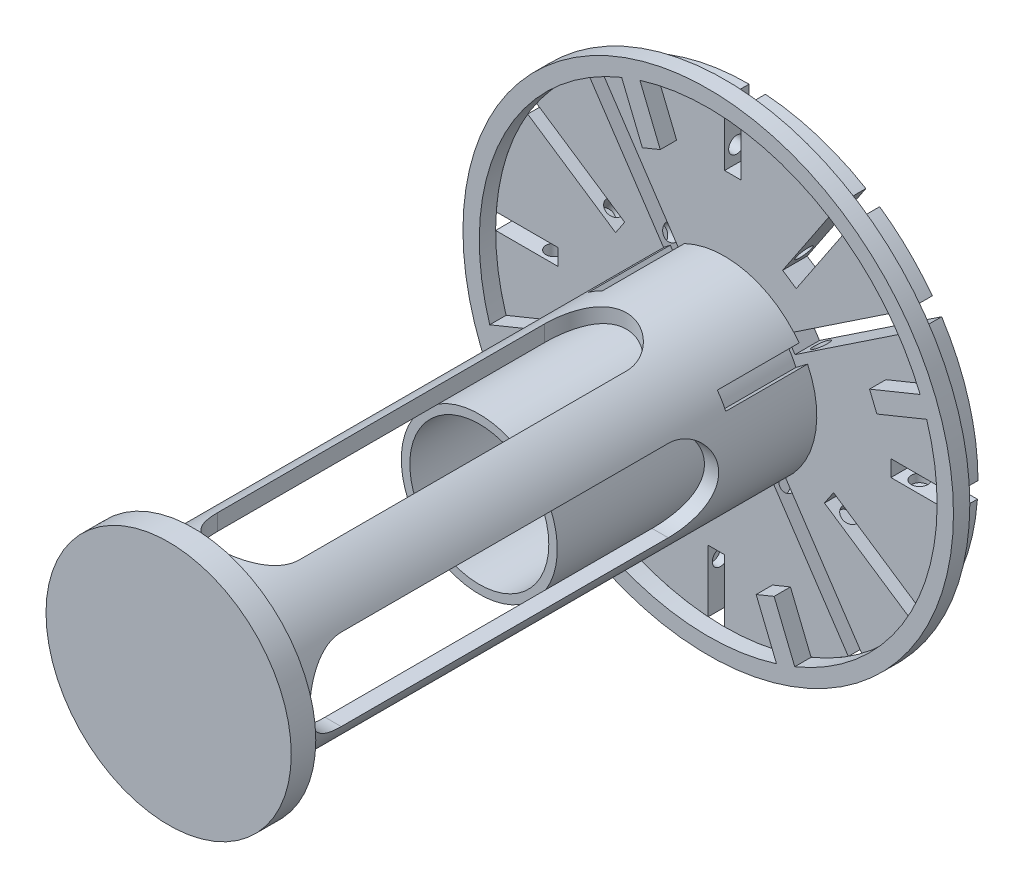
SolidWorks part; units mm, degrees
ref_plane "Front Plane" through (0, 0, 0) normal (0, 0, 1) x (1, 0, 0)
ref_plane "Top Plane" through (0, 0, 0) normal (0, 1, 0) x (1, 0, 0)
ref_plane "Right Plane" through (0, 0, 0) normal (1, 0, 0) x (0, 0, -1)
sketch "Sketch1" plane through (0, 0, 0) normal (0, 0, 1) x (1, 0, 0)
  line L0 (203.4844, -20.0194) -> (299.6235, -20.0194)
  line L1 (203.4844, -0.0194) -> (203.4844, -20.0194)
  line L2 (0.0194, 203.4844) -> (20.0194, 203.4844)
  line L3 (0.0194, 203.4844) -> (0.0194, 300.2915)
  line L5 (20.0194, 203.4844) -> (20.0194, 299.6235)
  line L6 (203.4844, -0.0194) -> (300.2915, -0.0194)
  line L7 (-20.0194, -203.4844) -> (-20.0194, -299.6235)
  line L8 (-0.0194, -203.4844) -> (-20.0194, -203.4844)
  line L9 (-0.0194, -203.4844) -> (-0.0194, -300.2915)
  line L10 (-203.4844, 20.0194) -> (-299.6235, 20.0194)
  line L11 (-203.4844, 0.0194) -> (-203.4844, 20.0194)
  line L12 (-203.4844, 0.0194) -> (-300.2915, 0.0194)
  line L13 (0, 0) -> (0, 203.4844) construction
  line L16 (0, 0) -> (203.4844, 0) construction
  line L18 (0, 0) -> (0, -203.4844) construction
  line L19 (0, 0) -> (-192.3667, -192.3667) construction
  line L20 (0, 0) -> (-203.4844, 0) construction
  line L22 (0, 0) -> (-59.8763, 80.6115) construction
  line L23 (0, 0) -> (-127.7407, 79.3401) construction
  line L26 (-133.2964, 71.0255) -> (-122.185, 87.6548)
  line L27 (-68.191, 75.0558) -> (-51.5616, 86.1672)
  line L30 (-122.185, 87.6548) -> (-246.8708, 170.9673)
  line L32 (-133.2964, 71.0255) -> (-257.7051, 154.1527)
  line L34 (-51.5616, 86.1672) -> (-162.6526, 252.4265)
  line L36 (-68.191, 75.0558) -> (-179.0968, 241.038)
  line L38 (75.0558, 68.191) -> (86.1672, 51.5616)
  line L39 (86.1672, 51.5616) -> (252.4265, 162.6526)
  line L40 (75.0558, 68.191) -> (241.038, 179.0968)
  line L41 (68.191, -75.0558) -> (51.5616, -86.1672)
  line L42 (51.5616, -86.1672) -> (162.6526, -252.4265)
  line L43 (68.191, -75.0558) -> (179.0968, -241.038)
  line L44 (-75.0558, -68.191) -> (-86.1672, -51.5616)
  line L45 (-86.1672, -51.5616) -> (-252.4265, -162.6526)
  line L46 (-75.0558, -68.191) -> (-241.038, -179.0968)
  line L47 (71.0255, 133.2964) -> (87.6548, 122.185)
  line L48 (87.6548, 122.185) -> (170.9673, 246.8708)
  line L49 (71.0255, 133.2964) -> (154.1527, 257.7051)
  line L50 (133.2964, -71.0255) -> (122.185, -87.6548)
  line L51 (122.185, -87.6548) -> (246.8708, -170.9673)
  line L52 (133.2964, -71.0255) -> (257.7051, -154.1527)
  line L53 (-71.0255, -133.2964) -> (-87.6548, -122.185)
  line L54 (-87.6548, -122.185) -> (-170.9673, -246.8708)
  line L55 (-71.0255, -133.2964) -> (-154.1527, -257.7051)
  line L56 (0, 0) -> (-212.3382, 212.3382) construction
  line L57 (0, 0) -> (212.3382, -212.3382) construction
  line L58 (0, 0) -> (212.3382, 212.3382) construction
  arc A13 (-257.7051, 154.1527) -> (-299.6235, 20.0194) centre (0, 0) ccw
  arc A14 (-179.0968, 241.038) -> (-246.8708, 170.9673) centre (0, 0) ccw
  arc A15 (0.0194, 300.2915) -> (-162.6526, 252.4265) centre (0, 0) ccw
  arc A16 (154.1527, 257.7051) -> (20.0194, 299.6235) centre (0, 0) ccw
  arc A17 (241.038, 179.0968) -> (170.9673, 246.8708) centre (0, 0) ccw
  arc A18 (300.2915, -0.0194) -> (252.4265, 162.6526) centre (0, 0) ccw
  arc A19 (257.7051, -154.1527) -> (299.6235, -20.0194) centre (0, 0) ccw
  arc A20 (179.0968, -241.038) -> (246.8708, -170.9673) centre (0, 0) ccw
  arc A21 (-0.0194, -300.2915) -> (162.6526, -252.4265) centre (0, 0) ccw
  arc A22 (-154.1527, -257.7051) -> (-20.0194, -299.6235) centre (0, 0) ccw
  arc A23 (-241.038, -179.0968) -> (-170.9673, -246.8708) centre (0, 0) ccw
  arc A24 (-300.2915, 0.0194) -> (-252.4265, -162.6526) centre (0, 0) ccw
  point P8 (10.0194, 203.4844)
  point P18 (0, 0)
  point P32 (0, 0)
  point P35 (0, 0)
  point P37 (0, 0)
  point P44 (-127.7407, 79.3401)
  point P47 (-59.8763, 80.6115)
  point P48 (-59.8763, 80.6115)
  point P60 (0, 0)
  point P79 (0, 0)
  point P81 (0, 0)
  point P94 (0, 0)
  dimension "D1" = 4
  dimension "D4" = 4
  dimension "D5" = 4
  dimension "D2" = 8
extrude "Boss-Extrude2" add sketch "Sketch1" along normal blind 30
sketch "Sketch5" plane through (4.1573, 2.7779, 0) normal (-0.8315, -0.5556, 0) x (0, 0, 1)
  line L0 (15, 100.2915) -> (15, 120.2915) construction
  line L1 (30, 100.2915) -> (0, 100.2915) construction
  circle A0 centre (15, 120.2915) radius 10
extrude "Cut-Extrude4" cut sketch "Sketch5" against normal blind 10 and the other way blind 40
sketch "Sketch6" plane through (20.0194, 0, 0) normal (-1, 0, 0) x (0, 0, 1)
  line L0 (15, 203.4844) -> (15, 223.4844) construction
  line L1 (30, 203.4844) -> (0, 203.4844) construction
  circle A0 centre (15, 223.4844) radius 10
extrude "Cut-Extrude5" cut sketch "Sketch6" against normal blind 10 and the other way blind 50
sketch "Sketch7" plane through (4.1573, -2.7779, 0) normal (-0.8315, 0.5556, 0) x (0, 0, 1)
  line L0 (15, 150.2915) -> (15, 170.2915) construction
  line L1 (30, 150.2915) -> (0, 150.2915) construction
  circle A0 centre (15, 170.2915) radius 10
extrude "Cut-Extrude6" cut sketch "Sketch7" against normal blind 10 and the other way blind 40
pattern_circular "CirPattern2" count 4 over 360 about axis through (0, 0, 0) along (0, 0, 1) of "Cut-Extrude4", "Cut-Extrude5", "Cut-Extrude6"
sketch "Sketch11" plane through (0, 0, 30) normal (0, 0, 1) x (1, 0, 0)
  circle A0 centre (0, 0) radius 85
extrude "Cut-Extrude7" cut sketch "Sketch11" against normal through all
sketch "Sketch12" plane through (0, 0, 30) normal (0, 0, 1) x (1, 0, 0)
  circle A0 centre (0, 0) radius 95.4191
  circle A1 centre (0, 0) radius 112.8034
extrude "Boss-Extrude4" add sketch "Sketch12" along normal blind 650
sketch "Sketch13" plane through (0, 0, 30) normal (0, 0, 1) x (1, 0, 0)
  line L2 (-252.4265, -162.6526) -> (-87.3025, -38.5108)
  line L3 (-179.0968, 241.038) -> (-55.9777, 77.2742)
  line L4 (170.9673, 246.8708) -> (87.6548, 122.185)
  line L5 (87.6548, 122.185) -> (71.0255, 133.2964)
  line L6 (71.0255, 133.2964) -> (154.1527, 257.7051)
  line L7 (20.0194, 299.6235) -> (20.0194, 203.4844)
  line L8 (-252.4265, -162.6526) -> (-96.4782, -58.4512)
  line L9 (-74.5857, 84.6261) -> (-179.0968, 241.038)
  line L10 (-246.8708, 170.9673) -> (-122.185, 87.6548)
  line L11 (-122.185, 87.6548) -> (-133.2964, 71.0255)
  line L12 (-133.2964, 71.0255) -> (-257.7051, 154.1527)
  line L13 (-299.6235, 20.0194) -> (-203.4844, 20.0194)
  line L14 (-203.4844, 20.0194) -> (-203.4844, 0.0194)
  line L15 (-203.4844, 0.0194) -> (-300.2915, 0.0194)
  line L18 (-246.8708, 170.9673) -> (-122.185, 87.6548)
  line L19 (-122.185, 87.6548) -> (-133.2964, 71.0255)
  line L20 (-133.2964, 71.0255) -> (-257.7051, 154.1527)
  line L21 (-299.6235, 20.0194) -> (-203.4844, 20.0194)
  line L22 (-203.4844, 20.0194) -> (-203.4844, 0.0194)
  line L23 (-203.4844, 0.0194) -> (-300.2915, 0.0194)
  line L24 (20.0194, 203.4844) -> (0.0194, 203.4844)
  line L25 (0.0194, 203.4844) -> (0.0194, 300.2915)
  line L26 (-162.6526, 252.4265) -> (-38.5108, 87.3025)
  line L27 (241.038, 179.0968) -> (77.2742, 55.9777)
  line L28 (246.8708, -170.9673) -> (122.185, -87.6548)
  line L29 (122.185, -87.6548) -> (133.2964, -71.0255)
  line L30 (133.2964, -71.0255) -> (257.7051, -154.1527)
  line L31 (299.6235, -20.0194) -> (203.4844, -20.0194)
  line L32 (203.4844, -20.0194) -> (203.4844, -0.0194)
  line L33 (203.4844, -0.0194) -> (300.2915, -0.0194)
  line L34 (252.4265, 162.6526) -> (87.3025, 38.5108)
  line L35 (179.0968, -241.038) -> (55.9777, -77.2742)
  line L36 (-170.9673, -246.8708) -> (-87.6548, -122.185)
  line L37 (-87.6548, -122.185) -> (-71.0255, -133.2964)
  line L38 (-71.0255, -133.2964) -> (-154.1527, -257.7051)
  line L39 (-20.0194, -299.6235) -> (-20.0194, -203.4844)
  line L40 (-20.0194, -203.4844) -> (-0.0194, -203.4844)
  line L41 (-0.0194, -203.4844) -> (-0.0194, -300.2915)
  line L42 (162.6526, -252.4265) -> (38.5108, -87.3025)
  line L43 (-241.038, -179.0968) -> (-77.2742, -55.9777)
  circle A0 centre (0, 0) radius 95.4191 construction
  arc A1 (-55.9777, 77.2742) -> (-87.3025, -38.5108) centre (0, 0) ccw
  arc A2 (241.038, 179.0968) -> (170.9673, 246.8708) centre (0, 0) ccw
  arc A3 (154.1527, 257.7051) -> (20.0194, 299.6235) centre (0, 0) ccw
  arc A4 (-74.5857, 84.6261) -> (-96.4782, -58.4512) centre (0, 0) ccw
  arc A5 (-179.0968, 241.038) -> (-246.8708, 170.9673) centre (0, 0) ccw
  arc A6 (-257.7051, 154.1527) -> (-299.6235, 20.0194) centre (0, 0) ccw
  arc A7 (-300.2915, 0.0194) -> (-252.4265, -162.6526) centre (0, 0) ccw
  arc A9 (-179.0968, 241.038) -> (-246.8708, 170.9673) centre (0, 0) ccw
  arc A10 (-257.7051, 154.1527) -> (-299.6235, 20.0194) centre (0, 0) ccw
  arc A11 (-300.2915, 0.0194) -> (-252.4265, -162.6526) centre (0, 0) ccw
  arc A12 (0.0194, 300.2915) -> (-162.6526, 252.4265) centre (0, 0) ccw
  arc A13 (77.2742, 55.9777) -> (-38.5108, 87.3025) centre (0, 0) ccw
  arc A14 (179.0968, -241.038) -> (246.8708, -170.9673) centre (0, 0) ccw
  arc A15 (257.7051, -154.1527) -> (299.6235, -20.0194) centre (0, 0) ccw
  arc A16 (300.2915, -0.0194) -> (252.4265, 162.6526) centre (0, 0) ccw
  arc A17 (55.9777, -77.2742) -> (87.3025, 38.5108) centre (0, 0) ccw
  arc A18 (-241.038, -179.0968) -> (-170.9673, -246.8708) centre (0, 0) ccw
  arc A19 (-154.1527, -257.7051) -> (-20.0194, -299.6235) centre (0, 0) ccw
  arc A20 (-0.0194, -300.2915) -> (162.6526, -252.4265) centre (0, 0) ccw
  arc A21 (-77.2742, -55.9777) -> (38.5108, -87.3025) centre (0, 0) ccw
  point P58 (0, 0)
  dimension "D1" = 0
  dimension "D2" = 4
extrude "Cut-Extrude8" cut sketch "Sketch13" along normal blind 100 flip side to cut
sketch "Sketch14" plane through (0, 0, 0) normal (0, 1, 0) x (1, 0, 0)
  line L0 (0, -680) -> (0, -600) construction
  line L1 (-112.8034, -680) -> (112.8034, -680) construction
  line L2 (0, -600) -> (0, -200) construction
  line L3 (-50, -600) -> (-50, -200)
  line L4 (50, -600) -> (50, -200)
  arc A0 (-50, -600) -> (50, -600) centre (0, -600) ccw
  arc A1 (50, -200) -> (-50, -200) centre (0, -200) ccw
  point P5 (0, -400)
extrude "Cut-Extrude9" cut sketch "Sketch14" against normal blind 120 and the other way blind 120
sketch "Sketch15" plane through (0, 0, 0) normal (1, 0, 0) x (0, 0, -1)
  line L0 (-680, 0) -> (-600, 0) construction
  line L1 (-680, 112.8034) -> (-680, -112.8034) construction
  line L2 (-600, 0) -> (-200, 0) construction
  line L3 (-600, 50) -> (-200, 50)
  line L4 (-600, -50) -> (-200, -50)
  arc A0 (-600, 50) -> (-600, -50) centre (-600, 0) ccw
  arc A1 (-200, -50) -> (-200, 50) centre (-200, 0) ccw
  point P6 (-400, 0)
extrude "Cut-Extrude10" cut sketch "Sketch15" against normal blind 120 and the other way blind 120
sketch "Sketch8" plane through (0, 0, 30) normal (0, 0, 1) x (1, 0, 0)
  circle A0 centre (0, 0) radius 85
  circle A1 centre (0, 0) radius 95.4191
extrude "Boss-Extrude3" add sketch "Sketch8" along normal blind 300
sketch "Sketch16" plane through (0, 0, 680) normal (0, 0, 1) x (1, 0, 0)
  circle A0 centre (0, 0) radius 150
extrude "Boss-Extrude5" add sketch "Sketch16" along normal blind 30
sketch "Sketch17" plane through (0, 0, 30) normal (0, 0, 1) x (1, 0, 0)
  circle A9 centre (0, 0) radius 280
  point P25 (0, 0)
extrude "Cut-Extrude11" cut sketch "Sketch17" against normal blind 40 flip side to cut
sketch "Sketch18" plane through (0, 0, 0) normal (0, 0, 1) x (1, 0, 0)
  line L0 (-105.8549, 259.2195) -> (-80.5872, 197.3434)
  line L1 (-80.5872, 197.3434) -> (-58.6589, 206.2981)
  line L2 (-58.6589, 206.2981) -> (-83.5472, 267.245)
  line L3 (197.3434, 80.5872) -> (206.2981, 58.6589)
  line L4 (206.2981, 58.6589) -> (267.245, 83.5472)
  line L5 (259.2195, 105.8549) -> (197.3434, 80.5872)
  line L6 (80.5872, -197.3434) -> (58.6589, -206.2981)
  line L7 (58.6589, -206.2981) -> (83.5472, -267.245)
  line L8 (105.8549, -259.2195) -> (80.5872, -197.3434)
  line L9 (-197.3434, -80.5872) -> (-206.2981, -58.6589)
  line L10 (-206.2981, -58.6589) -> (-267.245, -83.5472)
  line L11 (-259.2195, -105.8549) -> (-197.3434, -80.5872)
  arc A0 (-105.8549, 259.2195) -> (-267.245, -83.5472) centre (0, 0) ccw
  circle A1 centre (0, 0) radius 300
  arc A2 (259.2195, 105.8549) -> (-83.5472, 267.245) centre (0, 0) ccw
  arc A3 (105.8549, -259.2195) -> (267.245, 83.5472) centre (0, 0) ccw
  arc A4 (-259.2195, -105.8549) -> (83.5472, -267.245) centre (0, 0) ccw
  point P23 (0, 0)
  dimension "D1" = 4
extrude "Boss-Extrude9" add sketch "Sketch18" along normal blind 20 from surface at 30 separate body starting at face at (25.6456, 165.4754, 30)
